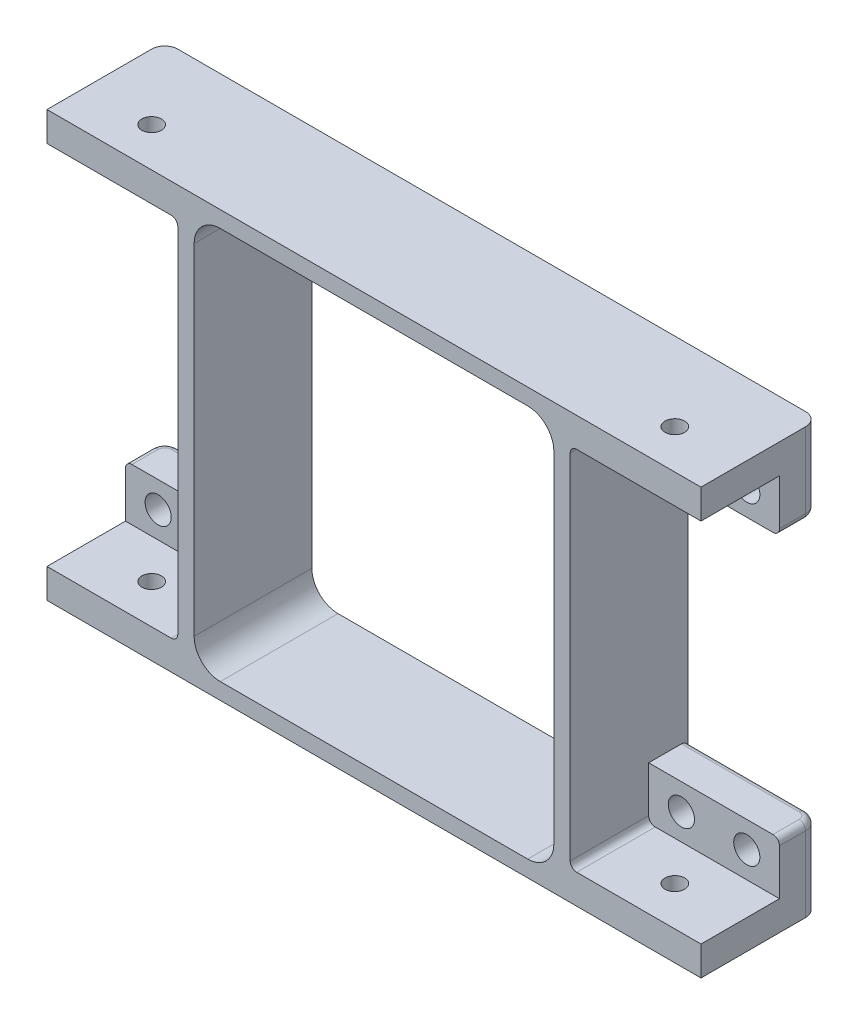
SolidWorks part; units mm, degrees
ref_plane "前视基准面" through (0, 0, 0) normal (0, 0, 1) x (1, 0, 0)
ref_plane "上视基准面" through (0, 0, 0) normal (0, 1, 0) x (1, 0, 0)
ref_plane "右视基准面" through (0, 0, 0) normal (1, 0, 0) x (0, 0, -1)
sketch "草图1" plane through (0, 0, 0) normal (0, 0, 1) x (1, 0, 0)
  line L1 (-50, -32.5) -> (50, -32.5)
  line L2 (-50, -32.5) -> (-50, 32.5)
  line L3 (-50, 32.5) -> (50, 32.5)
  line L4 (50, -32.5) -> (50, 32.5)
  line L5 (-50, -32.5) -> (50, 32.5) construction
  line L6 (-50, 32.5) -> (50, -32.5) construction
  point P0 (0, 0)
  dimension "D1" = 100
  dimension "D2" = 65
extrude "凸台-拉伸1" add sketch "草图1" along normal blind 18
sketch "草图2" plane through (0, 0, 18) normal (0, 0, 1) x (1, 0, 0)
  line L1 (-27.5, -30) -> (27.5, -30)
  line L2 (-27.5, -30) -> (-27.5, 30)
  line L3 (-27.5, 30) -> (27.5, 30)
  line L4 (27.5, -30) -> (27.5, 30)
  line L5 (-27.5, -30) -> (27.5, 30) construction
  line L6 (-27.5, 30) -> (27.5, -30) construction
  point P0 (0, 0)
  dimension "D1" = 55
  dimension "D2" = 60
extrude "切除-拉伸1" cut sketch "草图2" against normal through all
sketch "草图3" plane through (0, 0, 18) normal (0, 0, 1) x (1, 0, 0)
  line L0 (0, 0) -> (50, 0) construction
  line L1 (50, -32.5) -> (50, 32.5) construction
  line L3 (30, -28) -> (50, -28)
  line L4 (30, -28) -> (30, 28)
  line L5 (30, 28) -> (50, 28)
  line L6 (50, -28) -> (50, 28)
  line L7 (30, -28) -> (50, 28) construction
  line L8 (30, 28) -> (50, -28) construction
  point P5 (40, 0)
  dimension "D1" = 56
  dimension "D2" = 20
extrude "切除-拉伸2" cut sketch "草图3" against normal offset from surface (12 mm away) 6 up to face at (0, 0, 0)
sketch "草图4" plane through (0, 0, 6) normal (0, 0, 1) x (1, 0, 0)
  line L0 (50, -28) -> (50, 28) construction
  line L1 (30, -20) -> (50, -20)
  line L2 (30, -20) -> (30, 20)
  line L3 (30, 20) -> (50, 20)
  line L4 (50, -20) -> (50, 20)
  line L5 (30, -20) -> (50, 20) construction
  line L6 (30, 20) -> (50, -20) construction
  line L7 (30, 28) -> (30, -28) construction
  point P0 (40, 0)
  dimension "D1" = 40
extrude "切除-拉伸3" cut sketch "草图4" against normal through all
sketch "草图5" plane through (0, 0, 6) normal (0, 0, 1) x (1, 0, 0)
  line L0 (50, 20) -> (50, 28) construction
  line L1 (50, 20) -> (30, 20) construction
  line L2 (0, 0) -> (54.9836, 0) construction
  circle A0 centre (45, 24) radius 2
  circle A1 centre (35, 24) radius 2
  circle A2 centre (35, -24) radius 2
  circle A3 centre (45, -24) radius 2
  dimension "D1" = 5
  dimension "D2" = 4
  dimension "D3" = 10
  dimension "D4" = 4
extrude "切除-拉伸4" cut sketch "草图5" against normal through all
sketch "草图6" plane through (0, 32.5, 0) normal (0, 1, 0) x (1, 0, 0)
  line L0 (50, -18) -> (50, 0) construction
  line L1 (50, -18) -> (-50, -18) construction
  circle A0 centre (40, -12) radius 1.5
  dimension "D1" = 10
  dimension "D2" = 6
  dimension "D3" = 3
extrude "切除-拉伸5" cut sketch "草图6" against normal through all
mirror "镜向1" about plane through (0, 0, 0) normal (1, 0, 0) of "切除-拉伸5", "切除-拉伸3", "切除-拉伸4", "切除-拉伸2"
fillet "圆角1" radius 4 4 edges at (-27.5, 30, 9) (27.5, 30, 9) (27.5, -30, 9) (-27.5, -30, 9)
fillet "圆角2" radius 2 4 edges at (-50, -26.25, 0) (-50, 26.25, 0) (50, -26.25, 0) (50, 26.25, 0)
fillet "圆角3" radius 1 16 edges at (-39, -20, 0) (-49.4142, -20, 0.5858) (-39, 20, 0) (-49.4142, 20, 0.5858) (39, 20, 0) (49.4142, 20, 0.5858) (39, -20, 0) (49.4142, -20, 0.5858) (-50, -20, 4) (-50, 20, 4) (50, 20, 4) (50, -20, 4) (-30, -28, 12) (-30, 28, 12) (30, 28, 12) (30, -28, 12)
